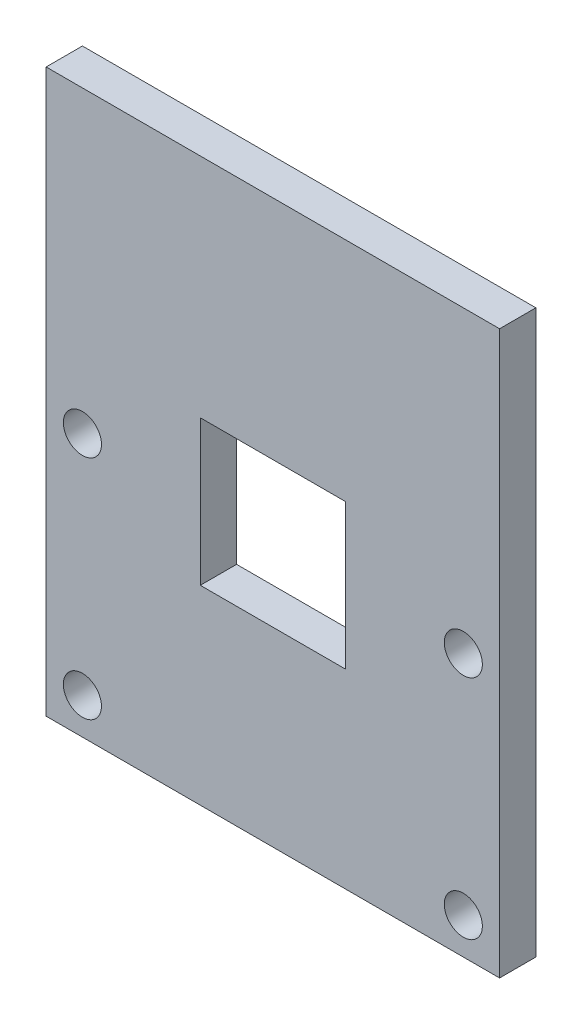
SolidWorks part; units mm, degrees
ref_plane "Plan de face" through (0, 0, 0) normal (0, 0, 1) x (1, 0, 0)
ref_plane "Plan de dessus" through (0, 0, 0) normal (0, 1, 0) x (1, 0, 0)
ref_plane "Plan de droite" through (0, 0, 0) normal (1, 0, 0) x (0, 0, -1)
sketch "Esquisse1" plane through (0, 0, 0) normal (0, 0, 1) x (1, 0, 0)
  line L0 (-23.7509, -30.4952) -> (-15.7509, -38.4952) construction
  line L1 (-32.2509, -17.9952) -> (-7.2509, -17.9952)
  line L2 (-32.2509, -17.9952) -> (-32.2509, -48.9952)
  line L3 (-32.2509, -48.9952) -> (-7.2509, -48.9952)
  line L4 (-7.2509, -17.9952) -> (-7.2509, -48.9952)
  line L5 (-23.7509, -30.4952) -> (-15.7509, -30.4952)
  line L6 (-23.7509, -30.4952) -> (-23.7509, -38.4952)
  line L7 (-23.7509, -38.4952) -> (-15.7509, -38.4952)
  line L8 (-15.7509, -30.4952) -> (-15.7509, -38.4952)
  line L9 (-15.7509, -30.4952) -> (-23.7509, -38.4952) construction
  circle A0 centre (-30.2509, -46.9952) radius 1.05
  circle A1 centre (-9.2509, -46.9952) radius 1.05
  circle A2 centre (-30.2509, -34.4952) radius 1.05
  circle A3 centre (-9.2509, -34.4952) radius 1.05
  point P16 (-19.7509, -34.4952)
  point P17 (0, 0)
  point P18 (0, 0)
  dimension "D3" = 2.1
  dimension "D4" = 2.1
  dimension "D5" = 2.1
  dimension "D6" = 2.1
  dimension "D16" = 2
  dimension "D1" = 31
  dimension "D2" = 25
  dimension "D7" = 2
  dimension "D8" = 2
  dimension "D9" = 21
  dimension "D10" = 12.5
  dimension "D11" = 2
  dimension "D12" = 21
  dimension "D13" = 2
  dimension "D14" = 2
  dimension "D15" = 12.5
  dimension "D17" = 8
  dimension "D18" = 8
  dimension "D19" = 10.5
  dimension "D20" = 0
extrude "Boss.-Extru.1" add sketch "Esquisse1" along normal blind 2
